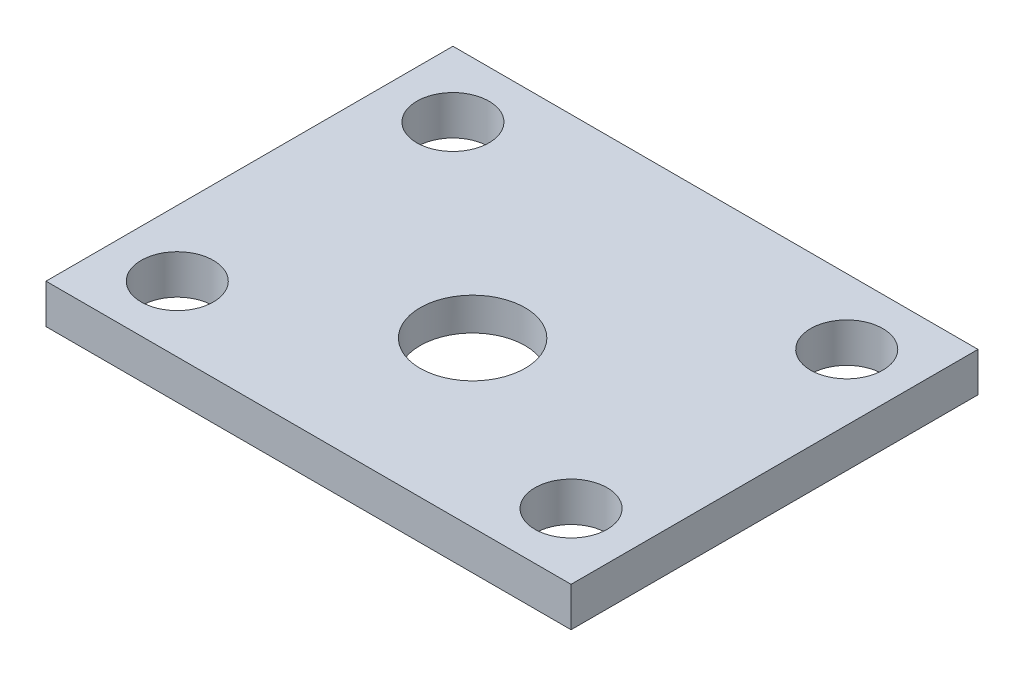
SolidWorks part; units mm, degrees
ref_plane "Front" through (0, 0, 0) normal (0, 0, 1) x (1, 0, 0)
ref_plane "Top" through (0, 0, 0) normal (0, 1, 0) x (1, 0, 0)
ref_plane "Right" through (0, 0, 0) normal (1, 0, 0) x (0, 0, -1)
sketch "Sketch1" plane through (0, 0, 0) normal (0, 1, 0) x (1, 0, 0)
  line L1 (-20, -15.5) -> (20, -15.5)
  line L2 (-20, -15.5) -> (-20, 15.5)
  line L3 (-20, 15.5) -> (20, 15.5)
  line L4 (20, -15.5) -> (20, 15.5)
  line L5 (-20, -15.5) -> (20, 15.5) construction
  line L6 (-20, 15.5) -> (20, -15.5) construction
  point P0 (0, 0)
  dimension "D1" = 40
  dimension "D2" = 31
extrude "Boss-Extrude1" add sketch "Sketch1" along normal blind 3
sketch "Sketch2" plane through (0, 3, 0) normal (0, 1, 0) x (1, 0, 0)
  line L0 (20, 15.5) -> (-20, 15.5) construction
  line L1 (-20, 15.5) -> (-20, -15.5) construction
  circle A0 centre (-15, 10.5) radius 2.75
  circle A1 centre (15, 10.5) radius 2.75
  circle A2 centre (15, -10.5) radius 2.75
  circle A3 centre (-15, -10.5) radius 2.75
  dimension "D3" = 5.5
  dimension "D1" = 5
  dimension "D2" = 5
  dimension "D4" = 2
  dimension "D5" = 2
extrude "Cut-Extrude1" cut sketch "Sketch2" against normal up to surface (3 mm away) up to face at (0, 0, 0)
sketch "Sketch3" plane through (0, 0, 0) normal (0, -1, 0) x (1, 0, 0)
  line L0 (-20, 15.5) -> (20, 15.5) construction
  line L3 (20, -15.5) -> (-20, -15.5) construction
  circle A0 centre (0, 3) radius 8.725
  point P8 (0, -15.5)
  dimension "D1" = 17.45
  dimension "D2" = 12.5
extrude "Cut-Extrude2" cut sketch "Sketch3" against normal blind 0.5
sketch "Sketch4" plane through (0, 3, 0) normal (0, 1, 0) x (1, 0, 0)
  line L0 (-20, -15.5) -> (20, -15.5) construction
  line L1 (20, 15.5) -> (-20, 15.5) construction
  circle A0 centre (0, -3) radius 4
  point P7 (0, 15.5)
  dimension "D2" = 8
  dimension "D1" = 12.5
extrude "Cut-Extrude3" cut sketch "Sketch4" against normal up to surface (2.5 mm away) up to face at (0, 0.5, -5.725)
